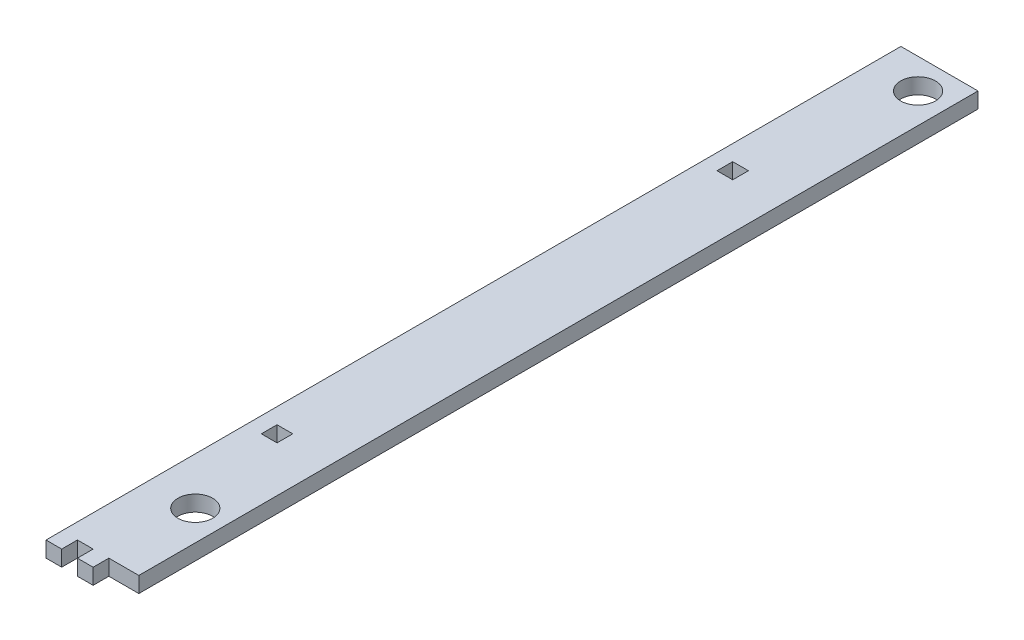
SolidWorks part; units mm, degrees
ref_plane "Front Plane" through (0, 0, 0) normal (0, 0, 1) x (1, 0, 0)
ref_plane "Top Plane" through (0, 0, 0) normal (0, 1, 0) x (1, 0, 0)
ref_plane "Right Plane" through (0, 0, 0) normal (1, 0, 0) x (0, 0, -1)
sketch "Axle Support Plate" plane through (0, 0, 0) normal (0, 1, 0) x (1, 0, 0)
  line L0 (19.05, 157.4574) -> (19.05, -134.6426) construction
  line L1 (6.35, 169.5676) -> (6.35, -175.9176) construction
  line L2 (12.7, -95.25) -> (12.7, -88.9)
  line L3 (6.35, 95.25) -> (12.7, 95.25)
  line L4 (31.1601, -169.5676) -> (31.1601, 169.5676)
  line L5 (0, 0) -> (31.1601, 169.5676) construction
  line L6 (0, 0) -> (31.1601, -169.5676) construction
  line L7 (0, 0) -> (31.1601, 0) construction
  line L8 (0, 169.5676) -> (31.1601, 169.5676)
  line L9 (6.35, -169.5676) -> (12.7, -169.5676)
  line L10 (6.35, 95.25) -> (6.35, 88.9)
  line L11 (6.35, 88.9) -> (12.7, 88.9)
  line L12 (0, -175.9176) -> (0, 169.5676)
  line L13 (12.7, 95.25) -> (12.7, 88.9)
  line L14 (6.35, -88.9) -> (12.7, -88.9)
  line L15 (6.35, -95.25) -> (6.35, -88.9)
  line L16 (6.35, -95.25) -> (12.7, -95.25)
  line L18 (0, -175.9176) -> (6.35, -175.9176)
  line L19 (6.35, -175.9176) -> (6.35, -169.5676)
  line L20 (12.7, -169.5676) -> (12.7, -175.9176)
  line L21 (12.7, -175.9176) -> (19.05, -175.9176)
  line L22 (19.05, -175.9176) -> (19.05, -169.5676)
  line L23 (19.05, -169.5676) -> (31.1601, -169.5676)
  circle A0 centre (19.05, 157.4574) radius 7.0301
  circle A1 centre (19.05, -134.6426) radius 7.0301
  point P0 (0, 0)
  dimension "D1" = 5.08
  dimension "D4" = 14.0603
  dimension "D5" = 5.08
  dimension "D8" = 88.9
  dimension "D14" = 14.0603
  dimension "D2" = 292.1
  dimension "D3" = 6.35
  dimension "D6" = 12.7
  dimension "D7" = 6.35
  dimension "D9" = 6.35
  dimension "D10" = 6.35
  dimension "D11" = 6.35
  dimension "D12" = 6.35
  dimension "D13" = 34.925
extrude "Boss-Extrude1" add sketch "Axle Support Plate" along normal blind 6.35
equation "\"Ball Diameter\"= 1.75in"
equation "\"Sheet Thickness\"= 0.25in"
equation "\"Screw Diameter\"= .17in"
equation "\"Robot Diameter\"= 16in"
equation "\"Castor Screw Diameter\"= 0.22in"
equation "\"Wheel Diameter\" = 4in"
equation "\"Nut Diameter\" = 8.4mm"
equation "\"Nut Height\" = 2.9mm"
equation "\"Screw Height\" = 0.55in"
equation "\"Pulley Diameter\" = 1in"
equation "\"Reactor Height\" = 14in"
equation "\"Elevator Height\" = 11.5in"
equation "\"Elevator Width\" = \"Ball Diameter\" + 0.25in"
equation "\"D2@Axle Support Plate\"=\"Elevator Height\""
equation "\"D1@Boss-Extrude1\"=\"Sheet Thickness\""
equation "\"Elevator Bearing Diameter\" = sqr(2*(\"Sheet Thickness\"^2)) + 0.2in"
equation "\"Elevator Axle Length\" = \"Elevator Width\" + 6*\"Sheet Thickness\""
equation "\"D4@Axle Support Plate\"=\"Elevator Bearing Diameter\""
equation "\"D6@Axle Support Plate\"=(\"Pulley Diameter\")/2"
equation "\"D3@Axle Support Plate\"=\"Sheet Thickness\""
equation "\"D7@Axle Support Plate\"=\"Sheet Thickness\""
equation "\"D10@Axle Support Plate\"=\"Sheet Thickness\""
equation "\"D11@Axle Support Plate\"=\"Sheet Thickness\""
equation "\"D12@Axle Support Plate\"=\"Sheet Thickness\""
equation "\"D13@Axle Support Plate\"=2.5in - \"Sheet Thickness\" - (\"Ball Diameter\")/2"
equation "\"D9@Axle Support Plate\"=\"Sheet Thickness\""
equation "\"D14@Axle Support Plate\"=\"Elevator Bearing Diameter\""
